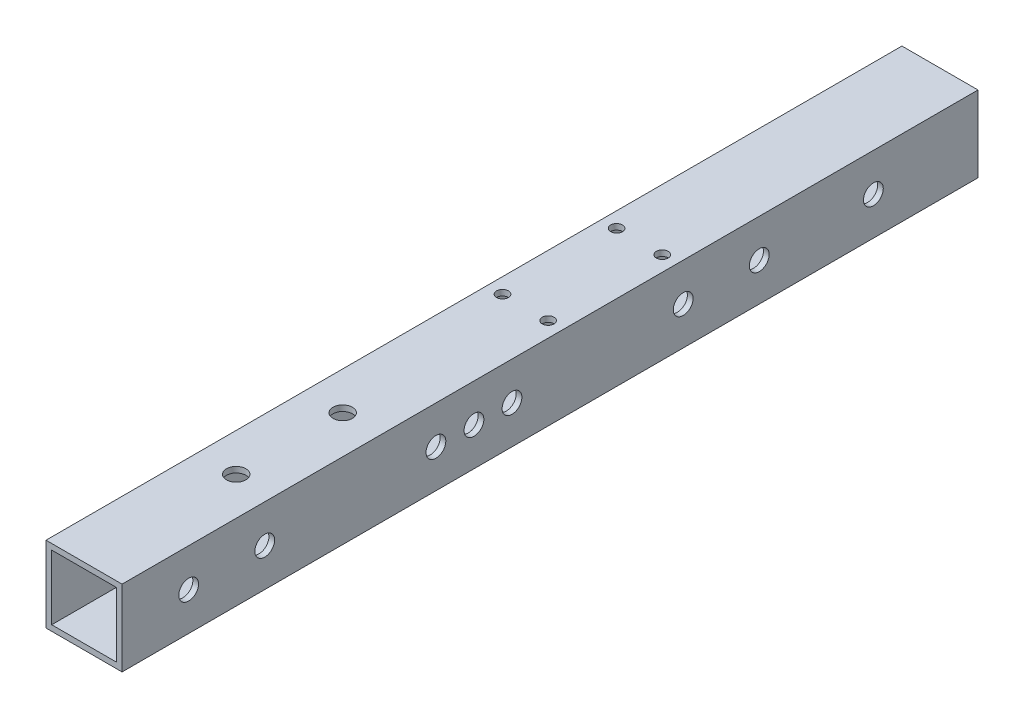
SolidWorks part; units mm, degrees
material "6061 合金"
ref_plane "前视基准面" through (0, 0, 0) normal (0, 0, 1) x (1, 0, 0)
ref_plane "上视基准面" through (0, 0, 0) normal (0, 1, 0) x (1, 0, 0)
ref_plane "右视基准面" through (0, 0, 0) normal (1, 0, 0) x (0, 0, -1)
sketch "草图1" plane through (0, 0, 0) normal (0, 0, 1) x (1, 0, 0)
  line L0 (-8.5, 8.5) -> (8.5, 8.5)
  line L1 (-10, 10) -> (10, 10)
  line L2 (-10, 10) -> (-10, -10)
  line L3 (-10, -10) -> (10, -10)
  line L4 (10, 10) -> (10, -10)
  line L5 (-10, 10) -> (10, -10) construction
  line L6 (-10, -10) -> (10, 10) construction
  line L7 (8.5, 8.5) -> (8.5, -8.5)
  line L8 (-8.5, -8.5) -> (8.5, -8.5)
  line L9 (-8.5, 8.5) -> (-8.5, -8.5)
  point P0 (0, 0)
  dimension "D1" = 20
  dimension "D2" = 1.5
extrude "凸台-拉伸1" add sketch "草图1" along normal mid plane 225
sketch "草图2" plane through (0, 10, 0) normal (0, 1, 0) x (1, 0, 0)
  circle A0 centre (0, -72.5) radius 2.55 construction
  circle A1 centre (0, -44.5) radius 2.55 construction
  circle A2 centre (0, -72.5) radius 2.55
  circle A3 centre (0, -44.5) radius 2.55
extrude "切除-拉伸1" cut sketch "草图2" against normal through all
sketch "草图3" plane through (10, 0, 0) normal (1, 0, 0) x (0, 0, -1)
  circle A1 centre (85, 0) radius 2.6
  circle A2 centre (85, 0) radius 2.6
  circle A3 centre (55, 0) radius 2.6
  circle A4 centre (55, 0) radius 2.6
  circle A5 centre (35, 0) radius 2.6
  circle A6 centre (35, 0) radius 2.6
  circle A7 centre (-10, 0) radius 2.6
  circle A8 centre (-10, 0) radius 2.6
  circle A9 centre (-20, 0) radius 2.6
  circle A10 centre (-20, 0) radius 2.6
  circle A11 centre (-30, 0) radius 2.6
  circle A12 centre (-30, 0) radius 2.6
  circle A13 centre (-75, 0) radius 2.6
  circle A14 centre (-75, 0) radius 2.6
  circle A15 centre (-95, 0) radius 2.6
  circle A16 centre (-95, 0) radius 2.6
  dimension "D1" = 0
  dimension "D2" = 0
  dimension "D3" = 0
  dimension "D4" = 0
  dimension "D5" = 0
  dimension "D6" = 0
  dimension "D7" = 0
  dimension "D8" = 0
extrude "切除-拉伸2" cut sketch "草图3" against normal through all
sketch "草图4" plane through (0, 10, 0) normal (0, 1, 0) x (1, 0, 0)
  line L0 (0, -112.5) -> (0, 18.5) construction
  line L1 (10, -112.5) -> (-10, -112.5) construction
  line L3 (-6, 33.5) -> (6, 33.5) construction
  line L4 (-6, 33.5) -> (-6, 3.5) construction
  line L5 (-6, 3.5) -> (6, 3.5) construction
  line L6 (6, 33.5) -> (6, 3.5) construction
  line L7 (-6, 33.5) -> (6, 3.5) construction
  line L8 (-6, 3.5) -> (6, 33.5) construction
  circle A0 centre (-6, 3.5) radius 1.55
  circle A1 centre (6, 3.5) radius 1.55
  circle A2 centre (-6, 33.5) radius 1.55
  circle A3 centre (6, 33.5) radius 1.55
  dimension "D4" = 3.1
  dimension "D1" = 12
  dimension "D2" = 30
  dimension "D3" = 131
extrude "切除-拉伸3" cut sketch "草图4" against normal through all
